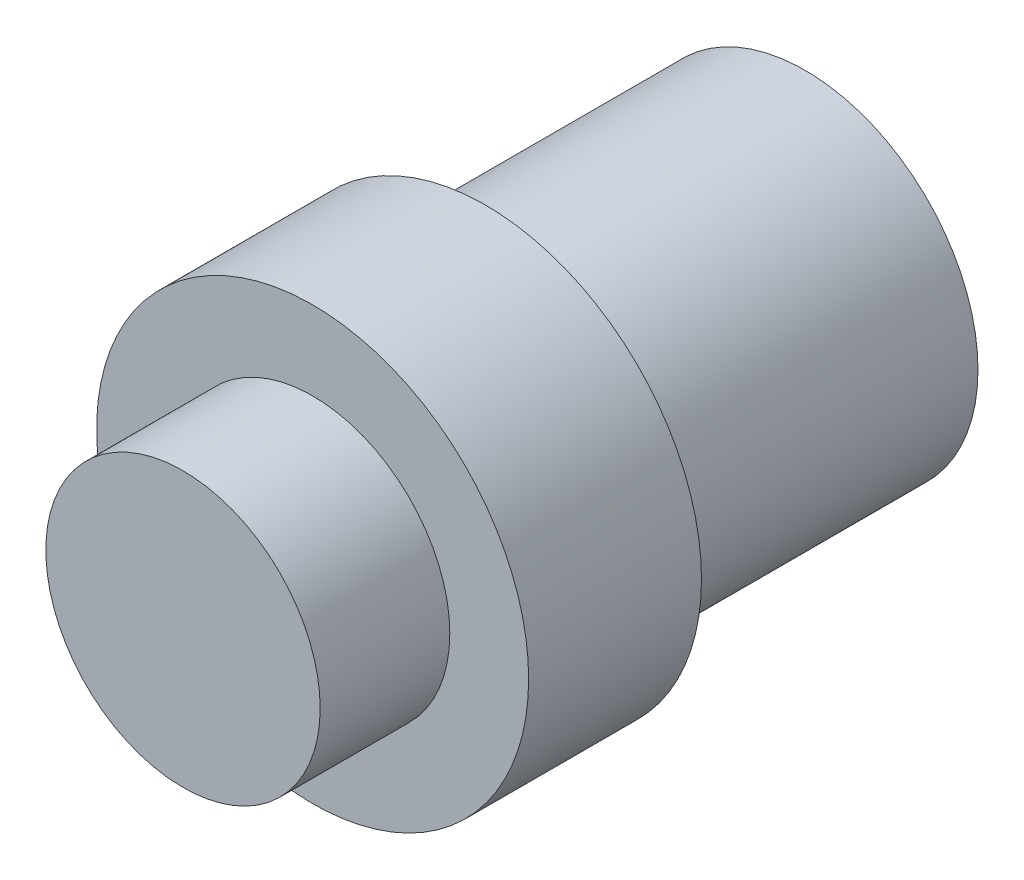
SolidWorks part; units mm, degrees
material "AISI 1020 Acero laminado en frío"
ref_plane "Alzado" through (0, 0, 0) normal (0, 0, 1) x (1, 0, 0)
ref_plane "Planta" through (0, 0, 0) normal (0, 1, 0) x (1, 0, 0)
ref_plane "Vista lateral" through (0, 0, 0) normal (1, 0, 0) x (0, 0, -1)
sketch "Croquis1" plane through (0, 0, 0) normal (0, 0, 1) x (1, 0, 0)
  circle A0 centre (0, 0) radius 20
  dimension "D1" = 40
extrude "Saliente-Extruir2" add sketch "Croquis1" along normal mid plane 37
sketch "Croquis3" plane through (0, 0, 18.5) normal (0, 0, 1) x (1, 0, 0)
  circle A4 centre (0, 0) radius 25
  circle A5 centre (0, 0) radius 25
  dimension "D2" = 5
extrude "Saliente-Extruir3" add sketch "Croquis3" along normal blind 20
sketch "Croquis4" plane through (0, 0, 38.5) normal (0, 0, 1) x (1, 0, 0)
  circle A0 centre (0, 0) radius 15.875
  dimension "D1" = 31.75
extrude "Saliente-Extruir4" add sketch "Croquis4" along normal blind 15
